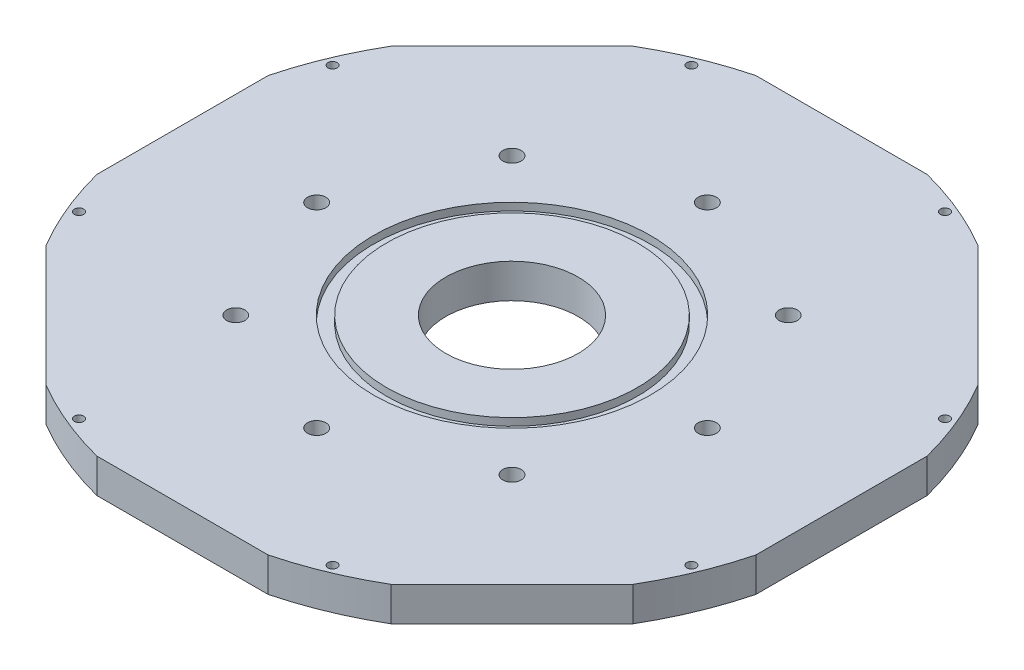
SolidWorks part; units mm, degrees
other "Markup1"
sketch "Sketch46" plane through (-122.3, 0, 122.3) normal (-0.1263, -0.9546, 0.2699) x (-0.172, -0.2469, -0.9537)
material "6061-T6 (SS)"
ref_plane "Front Plane" through (0, 0, 0) normal (0, 0, 1) x (1, 0, 0)
ref_plane "Top Plane" through (0, 0, 0) normal (0, 1, 0) x (1, 0, 0)
ref_plane "Right Plane" through (0, 0, 0) normal (1, 0, 0) x (0, 0, -1)
sketch "Sketch1" plane through (0, 0, 0) normal (0, 1, 0) x (1, 0, 0)
  line L1 (-50.6583, 122.3) -> (-122.3, 50.6583)
  line L2 (-122.3, 50.6583) -> (-122.3, -50.6583)
  line L3 (-122.3, -50.6583) -> (-50.6583, -122.3)
  line L4 (-50.6583, -122.3) -> (50.6583, -122.3)
  line L5 (50.6583, -122.3) -> (122.3, -50.6583)
  line L6 (122.3, -50.6583) -> (122.3, 50.6583)
  line L7 (122.3, 50.6583) -> (50.6583, 122.3)
  line L8 (50.6583, 122.3) -> (-50.6583, 122.3)
  circle A0 centre (0, 0) radius 122.3 construction
  circle A1 centre (0, 0) radius 126.365
  dimension "D2" = 252.73
  dimension "D1" = 244.6
extrude "Boss-Extrude1" add sketch "Sketch1" along normal blind 12.7 contours L4 A1 L5 L6 L7 L8 L1 L2 L3
sketch "Sketch3" plane through (0, 12.7, 0) normal (0, 1, 0) x (1, 0, 0)
  circle A0 centre (0, 0) radius 24.5745
  dimension "D1" = 49.149
extrude "Cut-Extrude1" cut sketch "Sketch3" against normal through all contours A0
sketch "Sketch5" plane through (0, 12.7, 0) normal (0, 1, 0) x (1, 0, 0)
  circle A0 centre (0, 0) radius 46.5455
  circle A1 centre (0, 0) radius 51.3715
  dimension "D1" = 93.091
  dimension "D2" = 102.743
extrude "Cut-Extrude2" cut sketch "Sketch5" against normal blind 2.794
sketch "Sketch19" plane through (0, 12.7, 0) normal (0, 1, 0) x (1, 0, 0)
  line L5 (-63.9978, 108.9605) -> (-31.7934, 122.3) construction
  line L6 (-47.8956, 115.6303) -> (-43.6974, 105.4949) construction
  circle A4 centre (0, 0) radius 122.9995
  circle A5 centre (-47.0699, 113.6367) radius 2.2479
  dimension "D1" = 4.4958
  dimension "D3" = 245.999
sketch "Sketch21" plane through (0, 12.7, 0) normal (0, 1, 0) x (1, 0, 0)
  point P0 (-72.5, 0)
  dimension "D1" = 72.5
hole_wizard "M8x1.25 Tapped Hole1" positions "Sketch22" profile "Sketch23" tap size "M8x1.25" standard "ANSI Metric"
sketch "Sketch22" plane through (0, 12.7, 0) normal (0, 1, 0) x (1, 0, 0)
  point P0 (-72.5, 0)
sketch "Sketch23" plane through (-72.5, 12.7, 0) normal (1, 0, 0) x (0, 0, 1)
  line L0 (0, 0) -> (0, 8.3929)
  line L1 (0, 8.3929) -> (3.4, 6.35)
  line L2 (3.4, 6.35) -> (3.4, 0)
  line L5 (3.4, 0) -> (0, 0)
  line L10 (0, 8.3929) -> (-3.4, 6.35) construction
  line L11 (0, -6.35) -> (0, 107.95) construction
  dimension "Tap Drill Dia." = 6.8
  dimension "Tap Drill Depth" = 6.35
  dimension "Drill Angle" = 118
cosmetic thread "Hole Thread2" parameters "D1"=6.35, "D2"=8
sketch "Sketch33" [suppressed] plane through (0, 19.05, 0) normal (0, 1, 0) x (1, 0, 0)
  circle A0 centre (-71.374, 0) radius 3.9687
  dimension "D1" = 7.9375
sketch "Sketch37" plane through (0, 0, 0) normal (0, -1, 0) x (1, 0, 0)
  circle A0 centre (0, 0) radius 119.0625
  circle A1 centre (0, 0) radius 115.2525
  dimension "D1" = 238.125
  dimension "D2" = 230.505
extrude "Cut-Extrude7" cut sketch "Sketch37" against normal blind 2.667
pattern_circular "CirPattern4" count 8 over 360 about axis through (0, 0, 0) along (0, 1, 0) of "M8x1.25 Tapped Hole1"
cosmetic thread "Hole Thread3" parameters "D1"=6.35, "D2"=8
cosmetic thread "Hole Thread4" parameters "D1"=6.35, "D2"=8
cosmetic thread "Hole Thread5" parameters "D1"=6.35, "D2"=8
cosmetic thread "Hole Thread6" parameters "D1"=6.35, "D2"=8
cosmetic thread "Hole Thread7" parameters "D1"=6.35, "D2"=8
cosmetic thread "Hole Thread8" parameters "D1"=6.35, "D2"=8
cosmetic thread "Hole Thread9" parameters "D1"=6.35, "D2"=8
hole_wizard "#8-32 Tapped Hole1" positions "Sketch47" profile "Sketch49" tap size "#8-32" standard "ANSI Inch" end condition through all
sketch "Sketch47" plane through (0, 12.7, 0) normal (0, 1, 0) x (1, 0, 0)
  point P0 (-47.0699, 113.6367)
sketch "Sketch49" plane through (-47.0699, 12.7, -113.6367) normal (1, 0, 0) x (0, 0, 1)
  line L0 (0, 0) -> (0, 12.7)
  line L1 (0, 12.7) -> (1.7272, 12.7)
  line L2 (1.7272, 12.7) -> (1.7272, 0)
  line L5 (1.7272, 0) -> (0, 0)
  line L11 (0, -6.35) -> (0, 107.95) construction
  dimension "Thru Tap Drill Dia." = 3.4544
  dimension "Thru Tap Drill Depth" = 12.7
cosmetic thread "Hole Thread10" parameters "D2"=4.1656
pattern_circular "CirPattern5" count 8 over 360 about axis through (0, 0, 0) along (0, 1, 0) of "#8-32 Tapped Hole1"
cosmetic thread "Hole Thread11" parameters "D2"=4.1656
cosmetic thread "Hole Thread12" parameters "D2"=4.1656
cosmetic thread "Hole Thread13" parameters "D2"=4.1656
cosmetic thread "Hole Thread14" parameters "D2"=4.1656
cosmetic thread "Hole Thread15" parameters "D2"=4.1656
cosmetic thread "Hole Thread16" parameters "D2"=4.1656
cosmetic thread "Hole Thread17" parameters "D2"=4.1656
